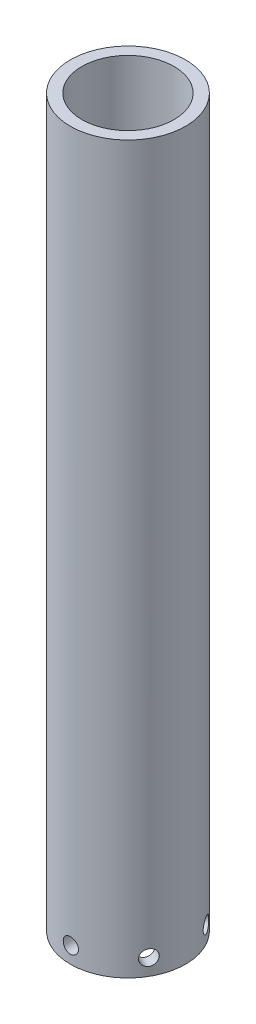
SolidWorks part; units mm, degrees
ref_plane "Front Plane" through (0, 0, 0) normal (0, 0, 1) x (1, 0, 0)
ref_plane "Top Plane" through (0, 0, 0) normal (0, 1, 0) x (1, 0, 0)
ref_plane "Right Plane" through (0, 0, 0) normal (1, 0, 0) x (0, 0, -1)
sketch "Sketch1" plane through (0, 0, 0) normal (0, 1, 0) x (1, 0, 0)
  circle A0 centre (0, 0) radius 15.875
  circle A1 centre (0, 0) radius 12.7
  dimension "D1" = 31.75
  dimension "D2" = 25.4
extrude "Boss-Extrude1" add sketch "Sketch1" along normal mid plane 200
sketch "Sketch2" plane through (0, 0, 0) normal (0, 0, 1) x (1, 0, 0)
  line L0 (-15.875, -100) -> (15.875, -100) construction
  circle A0 centre (0, -95.5) radius 2.1
  point P4 (0, 0)
  dimension "D2" = 4.2
  dimension "D1" = 4.5
extrude "Cut-Extrude1" cut sketch "Sketch2" against normal through all
pattern_circular "CirPattern1" count 6 over 360 about axis through (0, 100, 0) along (0, -1, 0) of "Cut-Extrude1"
